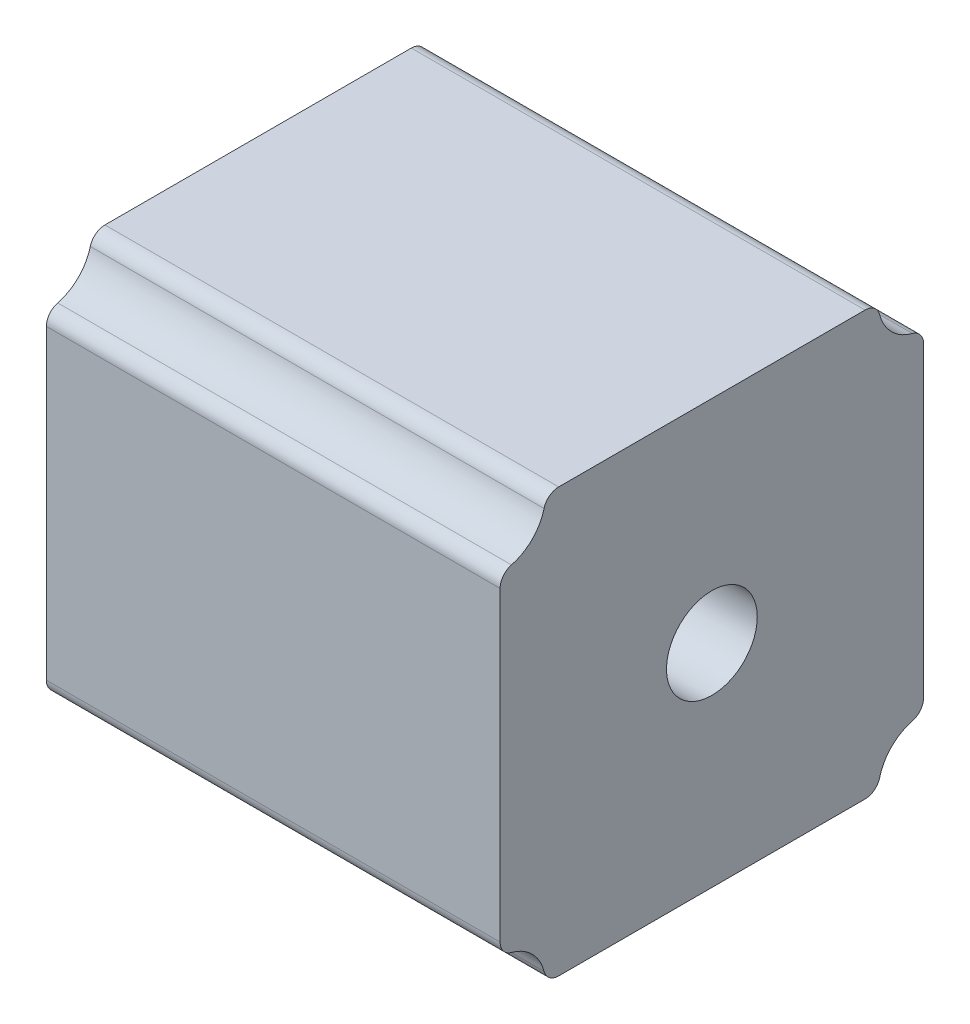
SolidWorks part; units mm, degrees
material "2024 合金"
ref_plane "前视基准面" through (0, 0, 0) normal (0, 0, 1) x (1, 0, 0)
ref_plane "上视基准面" through (0, 0, 0) normal (0, 1, 0) x (1, 0, 0)
ref_plane "右视基准面" through (0, 0, 0) normal (1, 0, 0) x (0, 0, -1)
sketch "草图1" plane through (0, 0, 0) normal (1, 0, 0) x (0, 0, -1)
  line L0 (-14, 10.127) -> (-14, -10.127)
  line L1 (-14, -14) -> (14, -14) construction
  line L2 (-14, -14) -> (-14, 14) construction
  line L3 (-14, 14) -> (14, 14) construction
  line L4 (14, -14) -> (14, 14) construction
  line L5 (-14, -14) -> (14, 14) construction
  line L6 (-14, 14) -> (14, -14) construction
  line L7 (-10.127, -14) -> (10.127, -14)
  line L8 (14, 10.127) -> (14, -10.127)
  line L9 (10.127, 14) -> (-10.127, 14)
  circle A0 centre (-14, 14) radius 3 construction
  arc A1 (-13.25, 11.0953) -> (-11.0953, 13.25) centre (-14, 14) ccw
  arc A2 (11.0953, 13.25) -> (13.25, 11.0953) centre (14, 14) ccw
  arc A3 (13.25, -11.0953) -> (11.0953, -13.25) centre (14, -14) ccw
  arc A4 (-11.0953, -13.25) -> (-13.25, -11.0953) centre (-14, -14) ccw
  arc A5 (-13.25, 11.0953) -> (-14, 10.127) centre (-13, 10.127) ccw
  arc A6 (-13.25, -11.0953) -> (-14, -10.127) centre (-13, -10.127) cw
  arc A7 (-10.127, -14) -> (-11.0953, -13.25) centre (-10.127, -13) cw
  arc A8 (10.127, -14) -> (11.0953, -13.25) centre (10.127, -13) ccw
  arc A9 (13.25, -11.0953) -> (14, -10.127) centre (13, -10.127) ccw
  arc A10 (14, 10.127) -> (13.25, 11.0953) centre (13, 10.127) ccw
  arc A11 (11.0953, 13.25) -> (10.127, 14) centre (10.127, 13) ccw
  arc A12 (-10.127, 14) -> (-11.0953, 13.25) centre (-10.127, 13) ccw
  point P0 (0, 0)
  point P11 (-14, 11)
  point P21 (0, 0)
  point P36 (-11, 14)
  dimension "D3" = 6
  dimension "D5" = 1
  dimension "D6" = 1
  dimension "D1" = 28
  dimension "D2" = 28
  dimension "D4" = 4
extrude "凸台-拉伸1" add sketch "草图1" against normal blind 30
sketch "草图2" plane through (0, 0, 0) normal (1, 0, 0) x (0, 0, -1)
  circle A0 centre (0, 0) radius 3
  dimension "D1" = 6
extrude "切除-拉伸1" cut sketch "草图2" against normal blind 5
